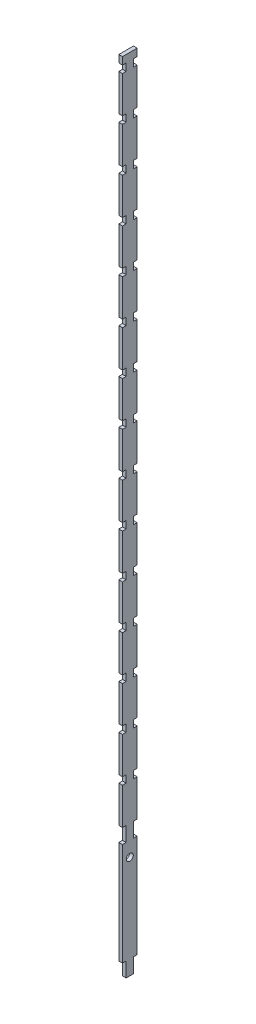
SolidWorks part; units mm, degrees
material "PVC 0.007 Plasticized"
ref_plane "Front Plane" through (0, 0, 0) normal (0, 0, 1) x (1, 0, 0)
ref_plane "Top Plane" through (0, 0, 0) normal (0, 1, 0) x (1, 0, 0)
ref_plane "Right Plane" through (0, 0, 0) normal (1, 0, 0) x (0, 0, -1)
sketch "Sketch1" plane through (0, 0, 0) normal (0, 1, 0) x (1, 0, 0)
  line L1 (0, 0) -> (1.5875, 0)
  line L2 (0, 0) -> (0, 6.35)
  line L3 (0, 6.35) -> (1.5875, 6.35)
  line L4 (1.5875, 0) -> (1.5875, 6.35)
  dimension "D1" = 1.5875
  dimension "D2" = 6.35
extrude "Boss-Extrude1" add sketch "Sketch1" along normal blind 346.075
sketch "Sketch2" plane through (0, 0, 0) normal (-1, 0, 0) x (0, 0, 1)
  line L0 (-6.35, 50.8) -> (-4.7625, 50.8)
  line L1 (-6.35, 346.075) -> (-6.35, 0) construction
  line L2 (-4.7625, 50.8) -> (-4.7625, 57.15)
  line L3 (-4.7625, 57.15) -> (-6.35, 57.15)
  line L4 (-6.35, 57.15) -> (-6.35, 50.8)
  line L5 (-6.35, 0) -> (0, 0) construction
  line L6 (-6.35, 73.025) -> (-4.7625, 73.025)
  line L7 (-4.7625, 73.025) -> (-4.7625, 76.2)
  line L8 (-4.7625, 76.2) -> (-6.35, 76.2)
  line L9 (0, 342.9) -> (0, 339.725)
  line L10 (-1.5875, 342.9) -> (0, 342.9)
  line L11 (-6.35, 92.075) -> (-4.7625, 92.075)
  line L12 (-6.35, 76.2) -> (-6.35, 73.025)
  line L13 (-4.7625, 92.075) -> (-4.7625, 95.25)
  line L14 (-4.7625, 95.25) -> (-6.35, 95.25)
  line L15 (-6.35, 95.25) -> (-6.35, 92.075)
  line L16 (-1.5875, 339.725) -> (-1.5875, 342.9)
  line L17 (0, 339.725) -> (-1.5875, 339.725)
  line L18 (0, 323.85) -> (0, 320.675)
  line L19 (-1.5875, 323.85) -> (0, 323.85)
  line L20 (-1.5875, 320.675) -> (-1.5875, 323.85)
  line L21 (-6.35, 111.125) -> (-4.7625, 111.125)
  line L22 (-4.7625, 111.125) -> (-4.7625, 114.3)
  line L23 (-4.7625, 114.3) -> (-6.35, 114.3)
  line L24 (-6.35, 114.3) -> (-6.35, 111.125)
  line L25 (0, 320.675) -> (-1.5875, 320.675)
  line L26 (0, 304.8) -> (0, 301.625)
  line L27 (-1.5875, 304.8) -> (0, 304.8)
  line L28 (-1.5875, 301.625) -> (-1.5875, 304.8)
  line L29 (0, 301.625) -> (-1.5875, 301.625)
  line L30 (-6.35, 130.175) -> (-4.7625, 130.175)
  line L31 (-4.7625, 130.175) -> (-4.7625, 133.35)
  line L32 (-4.7625, 133.35) -> (-6.35, 133.35)
  line L33 (-6.35, 133.35) -> (-6.35, 130.175)
  line L34 (0, 285.75) -> (0, 282.575)
  line L35 (-1.5875, 285.75) -> (0, 285.75)
  line L36 (-1.5875, 282.575) -> (-1.5875, 285.75)
  line L37 (0, 282.575) -> (-1.5875, 282.575)
  line L38 (0, 266.7) -> (0, 263.525)
  line L39 (-6.35, 149.225) -> (-4.7625, 149.225)
  line L40 (-4.7625, 149.225) -> (-4.7625, 152.4)
  line L41 (-4.7625, 152.4) -> (-6.35, 152.4)
  line L42 (-6.35, 152.4) -> (-6.35, 149.225)
  line L43 (-1.5875, 266.7) -> (0, 266.7)
  line L44 (-1.5875, 263.525) -> (-1.5875, 266.7)
  line L45 (0, 263.525) -> (-1.5875, 263.525)
  line L46 (0, 247.65) -> (0, 244.475)
  line L47 (-1.5875, 247.65) -> (0, 247.65)
  line L48 (-6.35, 168.275) -> (-4.7625, 168.275)
  line L49 (-4.7625, 168.275) -> (-4.7625, 171.45)
  line L50 (-4.7625, 171.45) -> (-6.35, 171.45)
  line L51 (-6.35, 171.45) -> (-6.35, 168.275)
  line L52 (-1.5875, 244.475) -> (-1.5875, 247.65)
  line L53 (0, 244.475) -> (-1.5875, 244.475)
  line L54 (0, 228.6) -> (0, 225.425)
  line L55 (-1.5875, 228.6) -> (0, 228.6)
  line L56 (-1.5875, 225.425) -> (-1.5875, 228.6)
  line L57 (-6.35, 187.325) -> (-4.7625, 187.325)
  line L58 (-4.7625, 187.325) -> (-4.7625, 190.5)
  line L59 (-4.7625, 190.5) -> (-6.35, 190.5)
  line L60 (-6.35, 190.5) -> (-6.35, 187.325)
  line L61 (0, 225.425) -> (-1.5875, 225.425)
  line L62 (-1.5875, 0) -> (-1.5875, 6.35)
  line L63 (0, 6.35) -> (-1.5875, 6.35)
  line L64 (0, 0) -> (0, 6.35)
  line L65 (0, 0) -> (-1.5875, 0)
  line L66 (-6.35, 206.375) -> (-4.7625, 206.375)
  line L67 (-4.7625, 206.375) -> (-4.7625, 209.55)
  line L68 (-4.7625, 209.55) -> (-6.35, 209.55)
  line L69 (-6.35, 209.55) -> (-6.35, 206.375)
  line L70 (-6.35, 0) -> (-4.7625, 0)
  line L71 (-6.35, 0) -> (-6.35, 6.35)
  line L72 (-6.35, 6.35) -> (-4.7625, 6.35)
  line L73 (-4.7625, 0) -> (-4.7625, 6.35)
  line L74 (0, 209.55) -> (0, 206.375)
  line L75 (-1.5875, 209.55) -> (0, 209.55)
  line L76 (-1.5875, 206.375) -> (-1.5875, 209.55)
  line L77 (0, 206.375) -> (-1.5875, 206.375)
  line L78 (0, 190.5) -> (0, 187.325)
  line L79 (-1.5875, 190.5) -> (0, 190.5)
  line L80 (-1.5875, 187.325) -> (-1.5875, 190.5)
  line L81 (0, 187.325) -> (-1.5875, 187.325)
  line L82 (0, 171.45) -> (0, 168.275)
  line L83 (-6.35, 225.425) -> (-4.7625, 225.425)
  line L84 (-4.7625, 225.425) -> (-4.7625, 228.6)
  line L85 (-4.7625, 228.6) -> (-6.35, 228.6)
  line L86 (-6.35, 228.6) -> (-6.35, 225.425)
  line L87 (-1.5875, 171.45) -> (0, 171.45)
  line L88 (-1.5875, 168.275) -> (-1.5875, 171.45)
  line L89 (0, 168.275) -> (-1.5875, 168.275)
  line L90 (0, 152.4) -> (0, 149.225)
  line L91 (-1.5875, 152.4) -> (0, 152.4)
  line L92 (-6.35, 244.475) -> (-4.7625, 244.475)
  line L93 (-4.7625, 244.475) -> (-4.7625, 247.65)
  line L94 (-4.7625, 247.65) -> (-6.35, 247.65)
  line L95 (-6.35, 247.65) -> (-6.35, 244.475)
  line L96 (-1.5875, 149.225) -> (-1.5875, 152.4)
  line L97 (0, 149.225) -> (-1.5875, 149.225)
  line L98 (0, 133.35) -> (0, 130.175)
  line L99 (-1.5875, 133.35) -> (0, 133.35)
  line L100 (-1.5875, 130.175) -> (-1.5875, 133.35)
  line L101 (-6.35, 263.525) -> (-4.7625, 263.525)
  line L102 (-4.7625, 263.525) -> (-4.7625, 266.7)
  line L103 (-4.7625, 266.7) -> (-6.35, 266.7)
  line L104 (-6.35, 266.7) -> (-6.35, 263.525)
  line L105 (0, 130.175) -> (-1.5875, 130.175)
  line L106 (0, 114.3) -> (0, 111.125)
  line L107 (-1.5875, 114.3) -> (0, 114.3)
  line L108 (-1.5875, 111.125) -> (-1.5875, 114.3)
  line L109 (0, 111.125) -> (-1.5875, 111.125)
  line L110 (-6.35, 282.575) -> (-4.7625, 282.575)
  line L111 (-4.7625, 282.575) -> (-4.7625, 285.75)
  line L112 (-4.7625, 285.75) -> (-6.35, 285.75)
  line L113 (-6.35, 285.75) -> (-6.35, 282.575)
  line L114 (0, 95.25) -> (0, 92.075)
  line L115 (-1.5875, 95.25) -> (0, 95.25)
  line L116 (-1.5875, 92.075) -> (-1.5875, 95.25)
  line L117 (0, 76.2) -> (0, 73.025)
  line L118 (0, 92.075) -> (-1.5875, 92.075)
  line L119 (-6.35, 301.625) -> (-4.7625, 301.625)
  line L120 (-4.7625, 301.625) -> (-4.7625, 304.8)
  line L121 (-4.7625, 304.8) -> (-6.35, 304.8)
  line L122 (-6.35, 304.8) -> (-6.35, 301.625)
  line L123 (-1.5875, 76.2) -> (0, 76.2)
  line L124 (-1.5875, 73.025) -> (-1.5875, 76.2)
  line L125 (0, 73.025) -> (-1.5875, 73.025)
  line L126 (0, 57.15) -> (0, 50.8)
  line L127 (-1.5875, 57.15) -> (0, 57.15)
  line L128 (-6.35, 320.675) -> (-4.7625, 320.675)
  line L129 (-4.7625, 320.675) -> (-4.7625, 323.85)
  line L130 (-4.7625, 323.85) -> (-6.35, 323.85)
  line L131 (-6.35, 323.85) -> (-6.35, 320.675)
  line L132 (-1.5875, 50.8) -> (-1.5875, 57.15)
  line L133 (0, 50.8) -> (-1.5875, 50.8)
  line L137 (-6.35, 339.725) -> (-4.7625, 339.725)
  line L138 (-4.7625, 339.725) -> (-4.7625, 342.9)
  line L139 (-4.7625, 342.9) -> (-6.35, 342.9)
  line L140 (-6.35, 342.9) -> (-6.35, 339.725)
  line L157 (-3.175, 0) -> (-3.175, 72.2495) construction
  line L183 (-6.35, 358.775) -> (-4.7625, 358.775) [skipped]
  line L184 (-4.7625, 358.775) -> (-4.7625, 361.95) [skipped]
  line L185 (-4.7625, 361.95) -> (-6.35, 361.95) [skipped]
  line L186 (-6.35, 361.95) -> (-6.35, 358.775) [skipped]
  line L191 (-6.35, 377.825) -> (-4.7625, 377.825) [skipped]
  line L192 (-4.7625, 377.825) -> (-4.7625, 381) [skipped]
  line L193 (-4.7625, 381) -> (-6.35, 381) [skipped]
  line L194 (-6.35, 381) -> (-6.35, 377.825) [skipped]
  line L199 (-6.35, 396.875) -> (-4.7625, 396.875) [skipped]
  line L200 (-4.7625, 396.875) -> (-4.7625, 400.05) [skipped]
  line L201 (-4.7625, 400.05) -> (-6.35, 400.05) [skipped]
  line L202 (-6.35, 400.05) -> (-6.35, 396.875) [skipped]
  dimension "D1" = 1.5875
  dimension "D2" = 6.35
  dimension "D3" = 6.35
  dimension "D4" = 19.05
  dimension "D5" = 3.175
  dimension "D6" = 18
  dimension "D10" = 44.45
  dimension "D8" = 19.05
  dimension "D7" = 1
extrude "Cut-Extrude1" cut sketch "Sketch2" against normal through all
sketch "Sketch3" plane through (0, 0, 0) normal (-1, 0, 0) x (0, 0, 1)
  line L0 (-1.5875, 50.8) -> (-4.7625, 50.8) construction
  line L1 (-3.175, 44.45) -> (-3.175, 50.8) construction
  line L2 (-6.35, 44.45) -> (-3.175, 44.45) construction
  line L3 (-6.35, 50.8) -> (-6.35, 6.35) construction
  line L4 (-3.175, 44.45) -> (0, 44.45) construction
  line L5 (0, 346.075) -> (0, 342.9) construction
  circle A0 centre (-3.175, 44.45) radius 1.5
  dimension "D1" = 3
  dimension "D2" = 6.35
extrude "Cut-Extrude2" cut sketch "Sketch3" against normal blind 10
